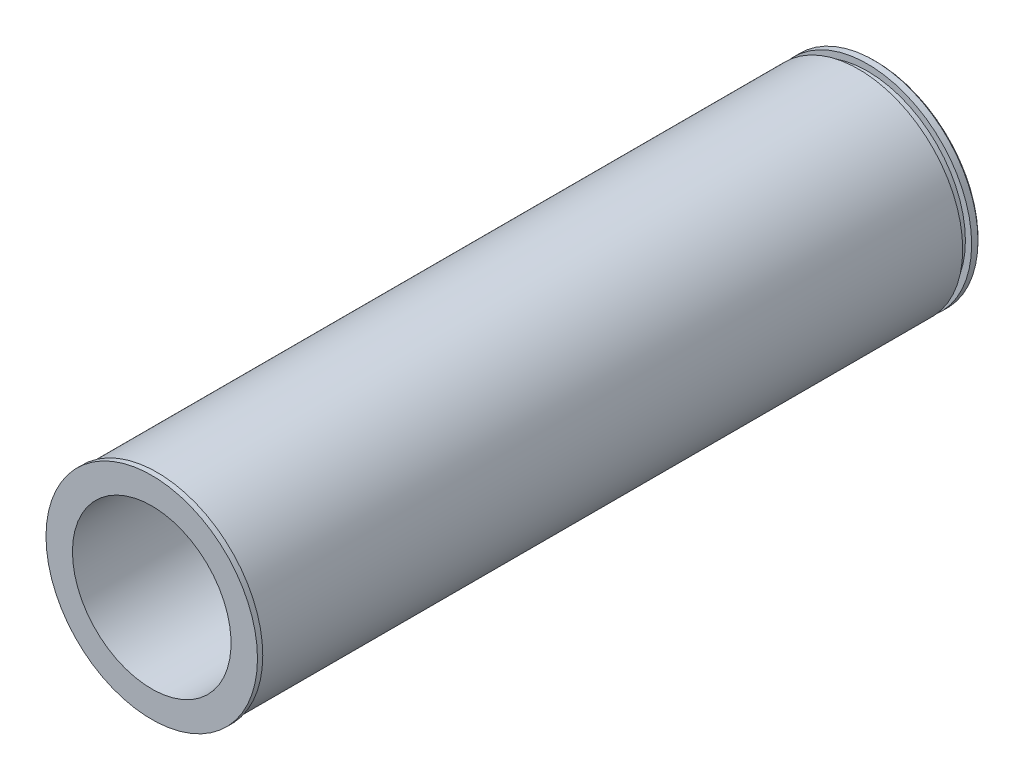
SolidWorks part; units mm, degrees
material "6061-T6 (SS)"
ref_plane "Front Plane" through (0, 0, 0) normal (0, 0, 1) x (1, 0, 0)
ref_plane "Top Plane" through (0, 0, 0) normal (0, 1, 0) x (1, 0, 0)
ref_plane "Right Plane" through (0, 0, 0) normal (1, 0, 0) x (0, 0, -1)
sketch "Sketch1" plane through (0, 0, 0) normal (1, 0, 0) x (0, 0, -1)
  line L0 (0, 0) -> (-47107.5785, 0) construction
  line L1 (-85.5345, 19.05) -> (88.4465, 19.05)
  line L3 (-84.2645, 25) -> (84.2645, 25)
  line L4 (84.2645, 23.5) -> (84.2645, 25)
  line L5 (-85.5345, 19.05) -> (-85.5345, -1.2889) construction
  line L8 (0, 25) -> (0, 0) construction
  line L11 (84.2645, 23.5) -> (86.4145, 23.5)
  line L12 (86.4145, 23.5) -> (86.4145, 25)
  line L13 (86.4145, 25) -> (88.4465, 25)
  line L14 (88.4465, 25) -> (88.4465, 19.05)
  line L21 (-85.5345, 19.05) -> (-85.5345, 25.4)
  line L22 (-85.5345, 25.4) -> (-84.2645, 25.4)
  line L23 (-84.2645, 25.4) -> (-84.2645, 25)
  dimension "D1" = 50
  dimension "D2" = 38.1
  dimension "D3" = 168.529
  dimension "D4" = 47
  dimension "D5" = 2.15
  dimension "D6" = 2.032
  dimension "D7" = 0.4
  dimension "D8" = 1.27
  dimension "D9" = 50.8
revolve "Revolve1" add sketch "Sketch1" angle 360 about L0
chamfer "Chamfer1" distance 0.508 angle 45 1 edges at (-25, 0, -88.4465)
